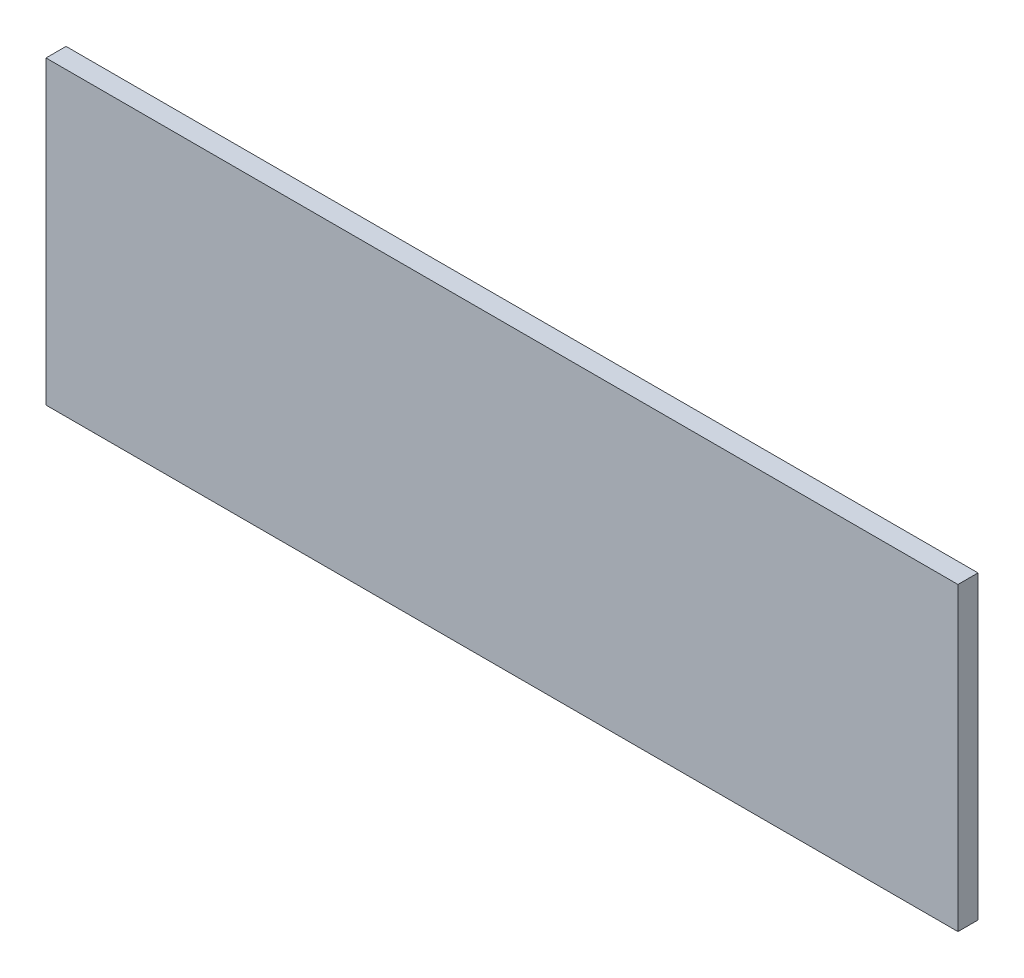
SolidWorks part; units mm, degrees
ref_plane "Alzado" through (0, 0, 0) normal (0, 0, 1) x (1, 0, 0)
ref_plane "Planta" through (0, 0, 0) normal (0, 1, 0) x (1, 0, 0)
ref_plane "Vista lateral" through (0, 0, 0) normal (1, 0, 0) x (0, 0, -1)
sketch "Croquis1" plane through (0, 0, 0) normal (0, 0, 1) x (1, 0, 0)
  line L1 (0, 0) -> (182, 0)
  line L2 (0, 0) -> (0, 60)
  line L3 (0, 60) -> (182, 60)
  line L4 (182, 0) -> (182, 60)
  dimension "D1" = 60
  dimension "D2" = 182
extrude "Saliente-Extruir1" add sketch "Croquis1" along normal mid plane 4
